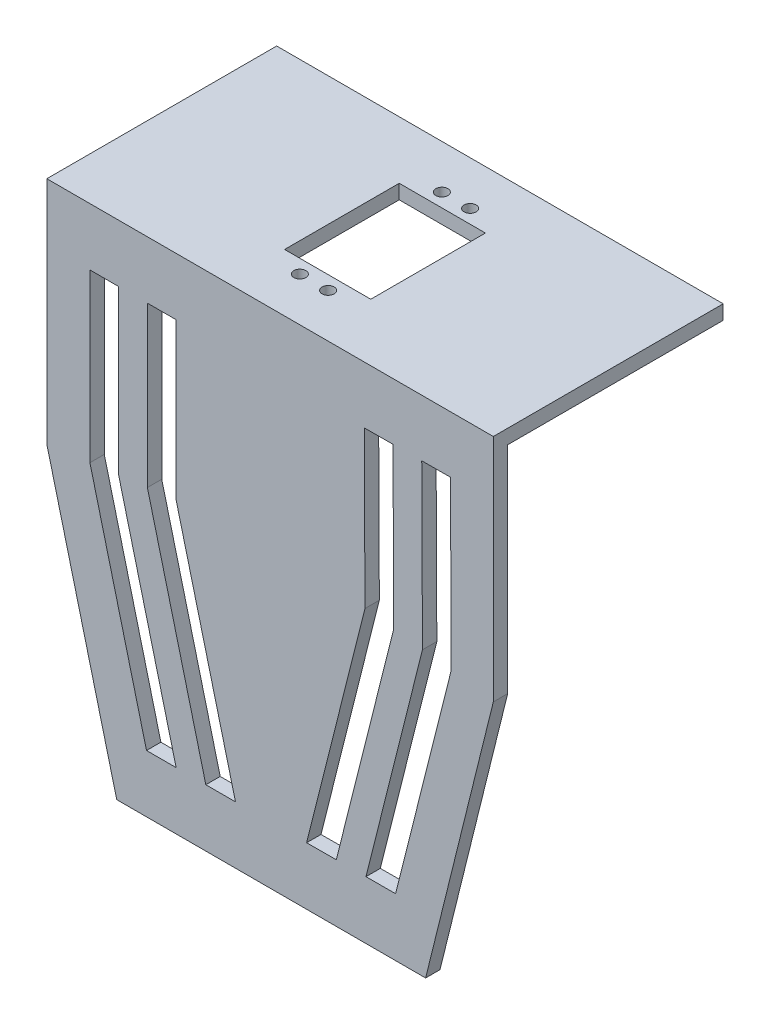
SolidWorks part; units mm, degrees
material "Aluminium 1050"
ref_plane "Front Plane" through (0, 0, 0) normal (0, 0, 1) x (1, 0, 0)
ref_plane "Top Plane" through (0, 0, 0) normal (0, 1, 0) x (1, 0, 0)
ref_plane "Right Plane" through (0, 0, 0) normal (1, 0, 0) x (0, 0, -1)
sketch "Sketch1" plane through (0, 0, 0) normal (0, 1, 0) x (1, 0, 0)
  line L0 (0, 0) -> (155.4, 0)
  line L1 (155.4, 0) -> (155.4, 80)
  line L2 (155.4, 80) -> (0, 80)
  line L3 (0, 80) -> (0, 0)
  dimension "D1" = 155.4
  dimension "D2" = 80
extrude "Boss-Extrude1" add sketch "Sketch1" along normal blind 5
sketch "Sketch2" plane through (0, 0, 0) normal (0, -1, 0) x (1, 0, 0)
  line L0 (0, 0) -> (155.4, 0)
  line L1 (155.4, 0) -> (155.4, -5)
  line L2 (155.4, 0) -> (155.4, -80) construction
  line L3 (155.4, -5) -> (0, -5)
  line L4 (0, -80) -> (0, 0) construction
  line L5 (0, -5) -> (0, 0)
  dimension "D1" = 5
extrude "Boss-Extrude2" add sketch "Sketch2" along normal blind 75
sketch "Sketch4" plane through (0, 0, 0) normal (0, 0, 1) x (1, 0, 0)
  line L1 (155.4, -75) -> (0, -75) construction
  line L2 (-0.1949, -71.393) -> (26.4446, -171.0861) construction
  line L3 (67, -165.7944) -> (14.5191, -171.198) construction
  line L8 (155.4, -75) -> (0.769, -75)
  line L9 (155.4, 20) -> (0.769, 20)
  line L10 (0, -75) -> (0.769, -75)
  line L11 (0, 20) -> (0.769, 20)
  line L12 (78.0845, -75) -> (78.0845, -180.3845) construction
  line L13 (24.329, -75) -> (24.329, -170) construction
  line L14 (24.329, -75) -> (24.329, -180.3845) construction
  line L15 (26.1543, -170.7944) -> (26.1543, -170)
  line L16 (131.84, -75) -> (131.84, -170) construction
  line L17 (131.84, -170) -> (24.329, -170)
  line L19 (0, -75) -> (24.329, -170)
  line L20 (155.4, -75) -> (131.84, -170)
  line L21 (131.84, -75) -> (131.84, -180.3845) construction
  line L22 (155.4, -170) -> (0.769, -170) construction
  line L23 (0, -170) -> (0.769, -170) construction
  dimension "D1" = 53.7555
  dimension "D2" = 53.7555
  dimension "D3" = 95
  dimension "D4" = 95
extrude "Boss-Extrude3" add sketch "Sketch4" against normal blind 5
sketch "Sketch6" plane through (0, 5, 0) normal (0, 1, 0) x (1, 0, 0)
  line L0 (0, 40) -> (155.4, 40)
  line L1 (0, 80) -> (0, 0) construction
  line L2 (155.4, 0) -> (155.4, 80) construction
  line L3 (77.7, 0) -> (77.7, 80)
  line L4 (0, 0) -> (155.4, 0) construction
  line L5 (155.4, 80) -> (0, 80) construction
  line L6 (0, 80) -> (155.4, 80)
  line L7 (0, 75) -> (155.4, 75)
  dimension "D1" = 5
sketch "Sketch7" plane through (0, 5, 0) normal (0, 1, 0) x (1, 0, 0)
  line L0 (82.7, 29.9) -> (72.7, 29.9) construction
  line L1 (92.7, 59.95) -> (62.7, 59.95)
  line L2 (92.7, 20.05) -> (62.7, 20.05)
  line L4 (77.7, 20.05) -> (77.7, 59.95)
  line L5 (77.7, 0) -> (77.7, 80) construction
  line L6 (92.7, 20.05) -> (92.7, 59.95)
  line L7 (62.7, 20.05) -> (62.7, 59.95)
  circle A0 centre (82.625, 64.7111) radius 2.1
  circle A1 centre (72.775, 64.7111) radius 2.1
  circle A2 centre (82.625, 15.2889) radius 2.1
  circle A3 centre (72.775, 15.2889) radius 2.1
  circle A4 centre (77.7, 29.9) radius 6.55
  dimension "D1" = 15
  dimension "D2" = 15
extrude "Cut-Extrude2" cut sketch "Sketch7" against normal up to next contours A4 L4 L2 L6 L1 | A4 L4 L1 L7 L2 | L4 A4 | L4 A4 | A2 | A3 | A1 | A0
sketch "Sketch8" plane through (0, 0, 0) normal (0, 0, 1) x (1, 0, 0)
  line L0 (77.7, 5) -> (78.0845, -170)
  line L1 (0, 5) -> (155.4, 5) construction
  line L2 (131.84, -170) -> (24.329, -170) construction
  line L3 (67.7, 4.978) -> (68.0845, -170.022)
  line L4 (87.7, 5.022) -> (88.0845, -169.978)
  line L5 (0, 5) -> (0, -75)
  line L6 (25, -15) -> (25, -71.8497)
  line L7 (25, -71.8497) -> (45.0139, -150)
  line L8 (35, -15) -> (35, -70.5895)
  line L9 (0, -75) -> (24.329, -170)
  line L10 (15, -15) -> (15, -73.1098)
  line L11 (15, -73.1098) -> (34.6912, -150)
  line L12 (35, -70.5895) -> (55.3366, -150)
  line L13 (45, -15) -> (45, -69.3294)
  line L14 (45, -69.3294) -> (65.6593, -150)
  line L15 (0, 5) -> (155.4, 5)
  line L16 (15, -15) -> (45, -15)
  line L17 (24.329, -170) -> (131.84, -170)
  line L18 (34.6912, -150) -> (65.6593, -150)
  line L19 (15, 5) -> (15, -73.1098) construction
  line L20 (0, -15) -> (155.4, -15) construction
  line L21 (25, 5) -> (25, -71.8497) construction
  line L22 (35, 5) -> (35, -70.5895) construction
  line L23 (45, 5) -> (45, -69.3294) construction
  line L24 (24.329, -150) -> (131.84, -150) construction
  line L25 (15, -73.1098) -> (38.86, -166.2787) construction
  line L26 (25, -71.8497) -> (48.5474, -163.7978) construction
  line L27 (35, -70.5895) -> (58.2348, -161.3169) construction
  line L28 (45, -69.3294) -> (67.9222, -158.836) construction
  line L29 (121.3895, -149.8095) -> (90.4217, -149.9456)
  line L30 (130.4874, -14.7682) -> (130.7372, -71.6173)
  line L31 (140.4873, -14.7243) -> (140.7426, -72.8335)
  line L32 (140.4873, -14.7243) -> (110.4876, -14.8561)
  line L33 (110.7263, -69.185) -> (90.4217, -149.9456)
  line L34 (110.4876, -14.8561) -> (110.7263, -69.185)
  line L35 (120.7317, -70.4012) -> (100.7443, -149.9002)
  line L36 (140.7426, -72.8335) -> (121.3895, -149.8095)
  line L37 (120.4875, -14.8122) -> (120.7317, -70.4012)
  line L38 (130.7372, -71.6173) -> (111.0669, -149.8549)
  dimension "D1" = 10
  dimension "D2" = 10
  dimension "D3" = 10
  dimension "D4" = 10
  dimension "D5" = 15
  dimension "D6" = 10
  dimension "D7" = 20
  dimension "D8" = 20
extrude "Cut-Extrude3" cut sketch "Sketch8" against normal up to next contours L11 L18 L7 L6 L16 L10 | L12 L18 L14 L13 L16 L8 | L37 L32 L34 L33 L29 L35 | L30 L38 L29 L36 L31 L32
